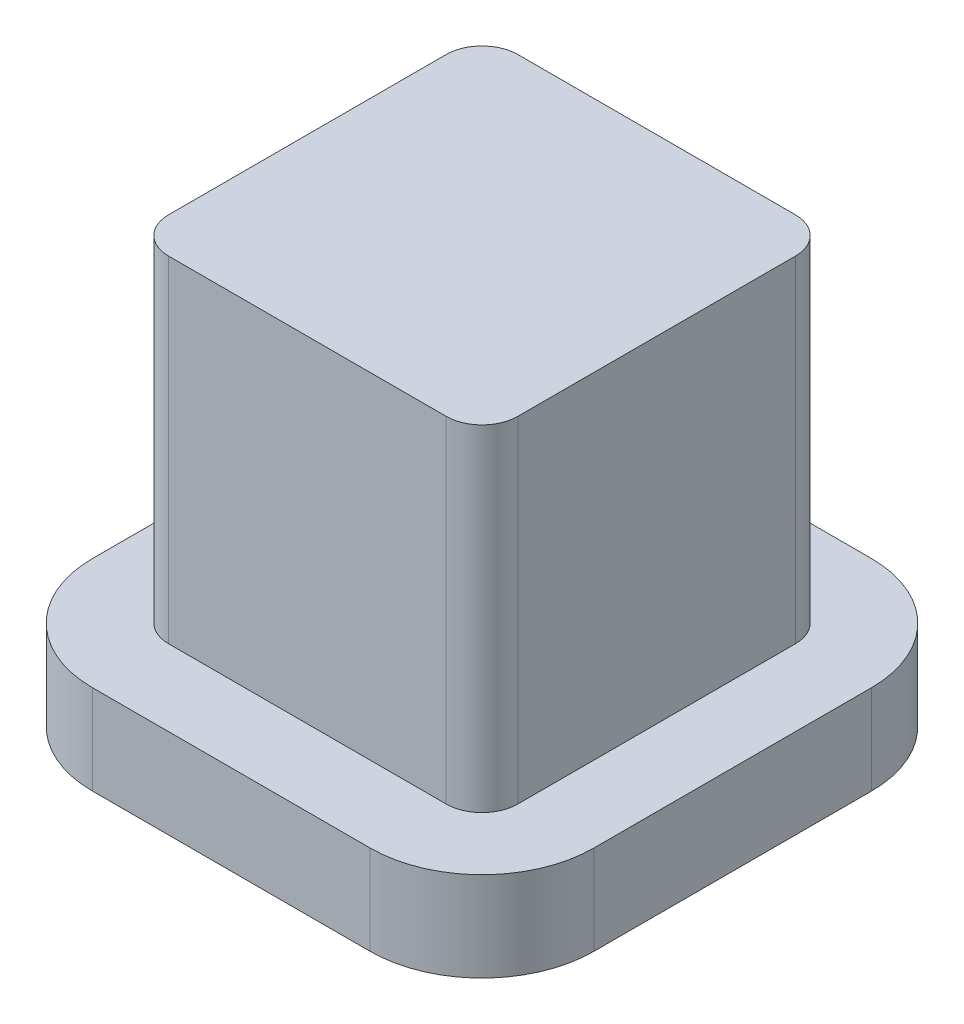
SolidWorks part; units mm, degrees
ref_plane "Front Plane" through (0, 0, 0) normal (0, 0, 1) x (1, 0, 0)
ref_plane "Top Plane" through (0, 0, 0) normal (0, 1, 0) x (1, 0, 0)
ref_plane "Right Plane" through (0, 0, 0) normal (1, 0, 0) x (0, 0, -1)
sketch "Sketch1" plane through (0, 123.7242, 0) normal (0, -1, 0) x (1, 0, 0)
  line L0 (88.9764, 216.9461) -> (88.9764, 210.7461) construction
  line L1 (80.7764, 210.7461) -> (80.7764, 216.9461) construction
  line L2 (81.7764, 217.9461) -> (87.9764, 217.9461) construction
  line L3 (87.9764, 209.7461) -> (81.7764, 209.7461) construction
  line L4 (80.7764, 210.7461) -> (80.7764, 216.9461) construction
  line L5 (81.7764, 217.9461) -> (87.9764, 217.9461) construction
  line L6 (88.9764, 216.9461) -> (88.9764, 210.7461) construction
  line L7 (87.9764, 209.7461) -> (81.7764, 209.7461) construction
  line L8 (80.9764, 210.7461) -> (80.9764, 216.9461)
  line L9 (81.7764, 217.7461) -> (87.9764, 217.7461)
  line L10 (88.7764, 216.9461) -> (88.7764, 210.7461)
  line L11 (87.9764, 209.9461) -> (81.7764, 209.9461)
  arc A0 (80.7764, 210.7461) -> (81.7764, 209.7461) centre (81.7764, 210.7461) ccw construction
  arc A1 (81.7764, 217.9461) -> (80.7764, 216.9461) centre (81.7764, 216.9461) ccw construction
  arc A2 (88.9764, 216.9461) -> (87.9764, 217.9461) centre (87.9764, 216.9461) ccw construction
  arc A3 (87.9764, 209.7461) -> (88.9764, 210.7461) centre (87.9764, 210.7461) ccw construction
  arc A4 (80.7764, 210.7461) -> (81.7764, 209.7461) centre (81.7764, 210.7461) ccw construction
  arc A5 (81.7764, 217.9461) -> (80.7764, 216.9461) centre (81.7764, 216.9461) ccw construction
  arc A6 (88.9764, 216.9461) -> (87.9764, 217.9461) centre (87.9764, 216.9461) ccw construction
  arc A7 (87.9764, 209.7461) -> (88.9764, 210.7461) centre (87.9764, 210.7461) ccw construction
  arc A8 (81.7764, 217.7461) -> (80.9764, 216.9461) centre (81.7764, 216.9461) ccw
  arc A9 (88.7764, 216.9461) -> (87.9764, 217.7461) centre (87.9764, 216.9461) ccw
  arc A10 (87.9764, 209.9461) -> (88.7764, 210.7461) centre (87.9764, 210.7461) ccw
  arc A11 (80.9764, 210.7461) -> (81.7764, 209.9461) centre (81.7764, 210.7461) ccw
  dimension "D1" = 0.2
extrude "Boss-Extrude1" add sketch "Sketch1" against normal blind 7.5 from offset 1
sketch "Sketch2" plane through (0, 122.7242, 0) normal (0, -1, 0) x (1, 0, 0)
  line L8 (81.7764, 208.2461) -> (87.9764, 208.2461)
  line L9 (90.4764, 210.7461) -> (90.4764, 216.9461)
  line L10 (87.9764, 219.4461) -> (81.7764, 219.4461)
  line L11 (79.2764, 216.9461) -> (79.2764, 210.7461)
  line L12 (81.7764, 208.2461) -> (87.9764, 208.2461)
  line L13 (90.4764, 210.7461) -> (90.4764, 216.9461)
  line L14 (87.9764, 219.4461) -> (81.7764, 219.4461)
  line L15 (79.2764, 216.9461) -> (79.2764, 210.7461)
  arc A8 (79.2764, 210.7461) -> (81.7764, 208.2461) centre (81.7764, 210.7461) ccw
  arc A9 (87.9764, 208.2461) -> (90.4764, 210.7461) centre (87.9764, 210.7461) ccw
  arc A10 (90.4764, 216.9461) -> (87.9764, 219.4461) centre (87.9764, 216.9461) ccw
  arc A11 (81.7764, 219.4461) -> (79.2764, 216.9461) centre (81.7764, 216.9461) ccw
  arc A12 (79.2764, 210.7461) -> (81.7764, 208.2461) centre (81.7764, 210.7461) ccw
  arc A13 (87.9764, 208.2461) -> (90.4764, 210.7461) centre (87.9764, 210.7461) ccw
  arc A14 (90.4764, 216.9461) -> (87.9764, 219.4461) centre (87.9764, 216.9461) ccw
  arc A15 (81.7764, 219.4461) -> (79.2764, 216.9461) centre (81.7764, 216.9461) ccw
  dimension "D1" = 1.7
extrude "Boss-Extrude2" add sketch "Sketch2" along normal blind 2
sketch "Sketch3" plane through (0, 120.7242, 0) normal (0, -1, 0) x (1, 0, 0)
  line L0 (81.7764, 208.2461) -> (87.9764, 208.2461) construction
  line L1 (87.9764, 210.7461) -> (81.7764, 210.7461)
  line L2 (87.9764, 210.7461) -> (87.9764, 216.9461)
  line L3 (87.9764, 216.9461) -> (81.7764, 216.9461)
  line L4 (81.7764, 210.7461) -> (81.7764, 216.9461)
  line L5 (87.9764, 219.4461) -> (81.7764, 219.4461) construction
  line L6 (79.2764, 216.9461) -> (79.2764, 210.7461) construction
  line L7 (90.4764, 210.7461) -> (90.4764, 216.9461) construction
  dimension "D1" = 2.5
  dimension "D2" = 2.5
  dimension "D3" = 2.5
  dimension "D4" = 2.5
extrude "Cut-Extrude1" cut sketch "Sketch3" against normal blind 4.4
